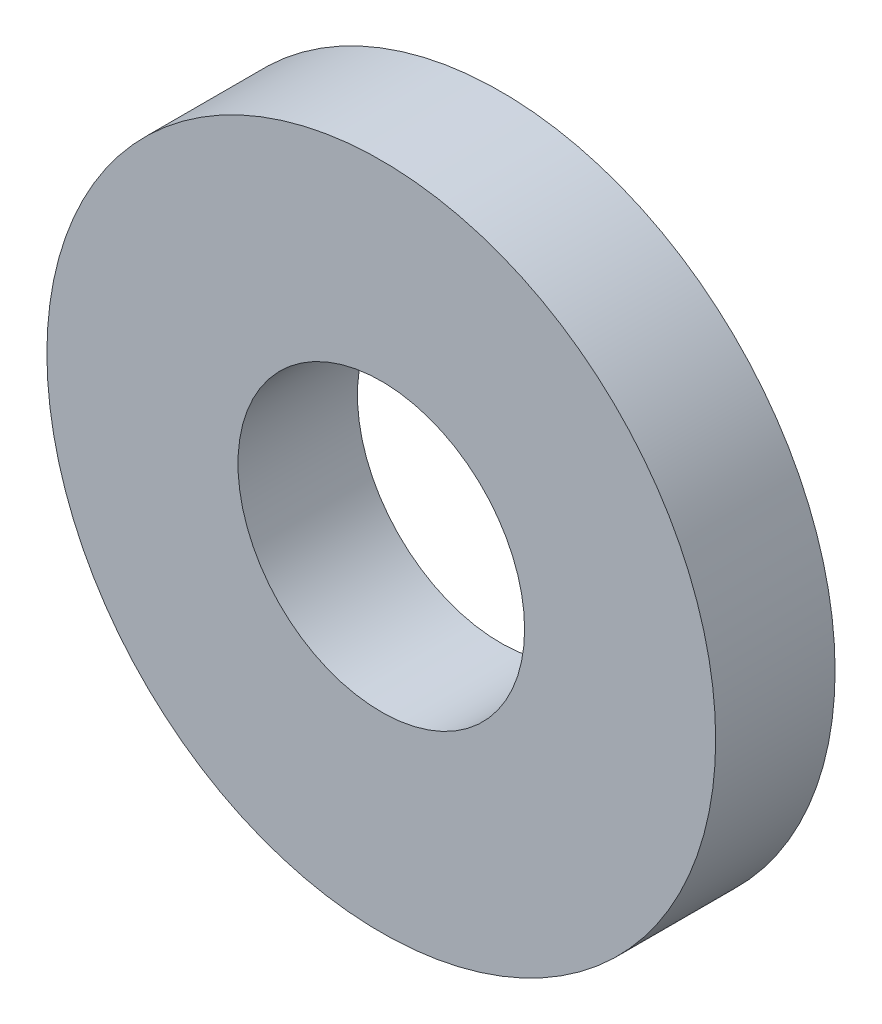
SolidWorks part; units mm, degrees
ref_plane "Front Plane" through (0, 0, 0) normal (0, 0, 1) x (1, 0, 0)
ref_plane "Top Plane" through (0, 0, 0) normal (0, 1, 0) x (1, 0, 0)
ref_plane "Right Plane" through (0, 0, 0) normal (1, 0, 0) x (0, 0, -1)
sketch "Sketch1" plane through (0, 0, 0) normal (0, 0, 1) x (1, 0, 0)
  circle A0 centre (0, 0) radius 3.81
  circle A1 centre (0, 0) radius 8.89
  dimension "D1" = 17.78
  dimension "D2" = 7.62
extrude "Boss-Extrude1" add sketch "Sketch1" along normal blind 3.175
